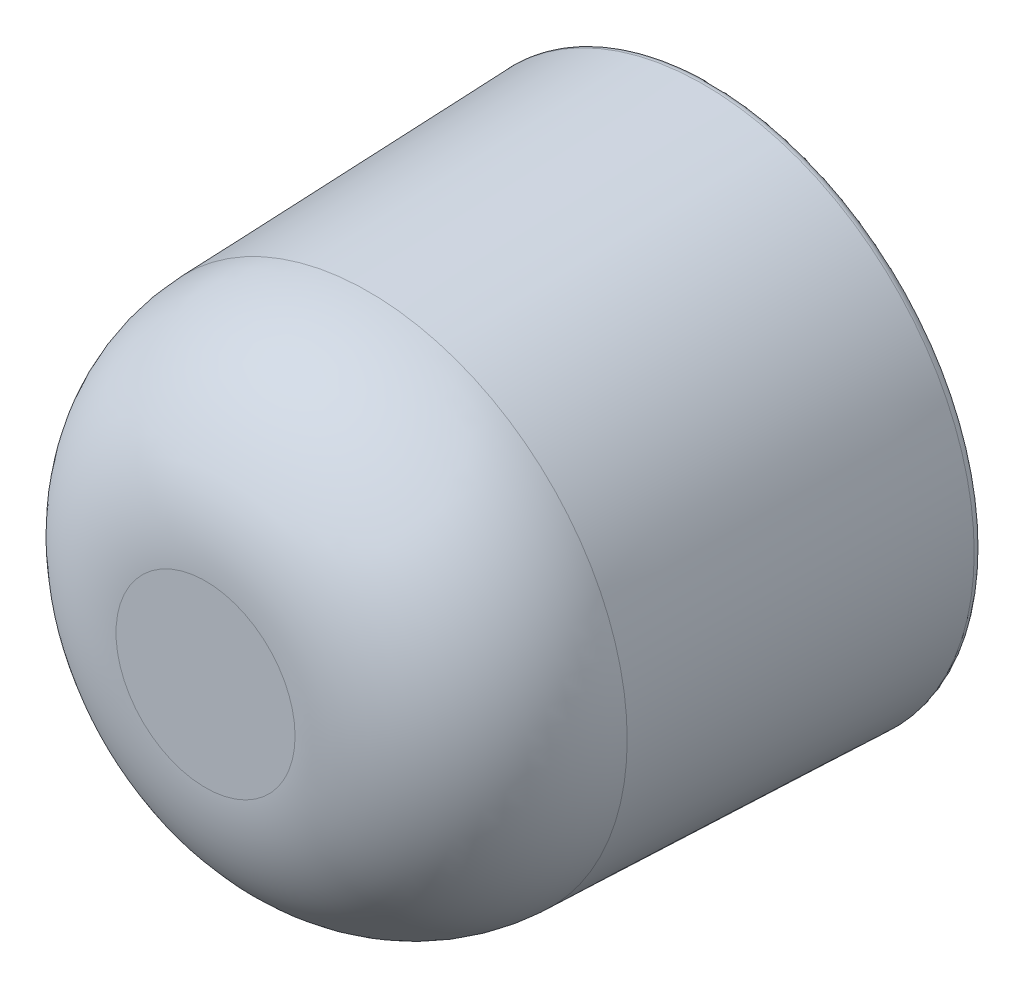
SolidWorks part; units mm, degrees
material "Plastique personnalisé"
ref_plane "Plan de face" through (0, 0, 0) normal (0, 0, 1) x (1, 0, 0)
ref_plane "Plan de dessus" through (0, 0, 0) normal (0, 1, 0) x (1, 0, 0)
ref_plane "Plan de droite" through (0, 0, 0) normal (1, 0, 0) x (0, 0, -1)
sketch "Esquisse1" plane through (0, 0, 0) normal (0, 0, 1) x (1, 0, 0)
  circle A0 centre (0, 0) radius 8
  dimension "D1" = 16
extrude "Boss.-Extru.1" add sketch "Esquisse1" along normal blind 15 draft 2
fillet "Congé1" radius 5 1 edges at (7.4762, 0, 15)
sketch "Esquisse2" plane through (0, 0, 0) normal (0, 0, -1) x (-1, 0, 0)
  circle A0 centre (0, 0) radius 3
extrude "Enlèv. mat.-Extru.1" cut sketch "Esquisse2" against normal blind 12
sketch "Esquisse3" plane through (0, 0, 0) normal (0, 0, -1) x (-1, 0, 0)
  circle A0 centre (0, 0) radius 7.5
  dimension "D1" = 15
extrude "Enlèv. mat.-Extru.2" cut sketch "Esquisse3" against normal blind 5
fillet "Congé2" radius 0.25 1 edges at (8, 0, 0)
